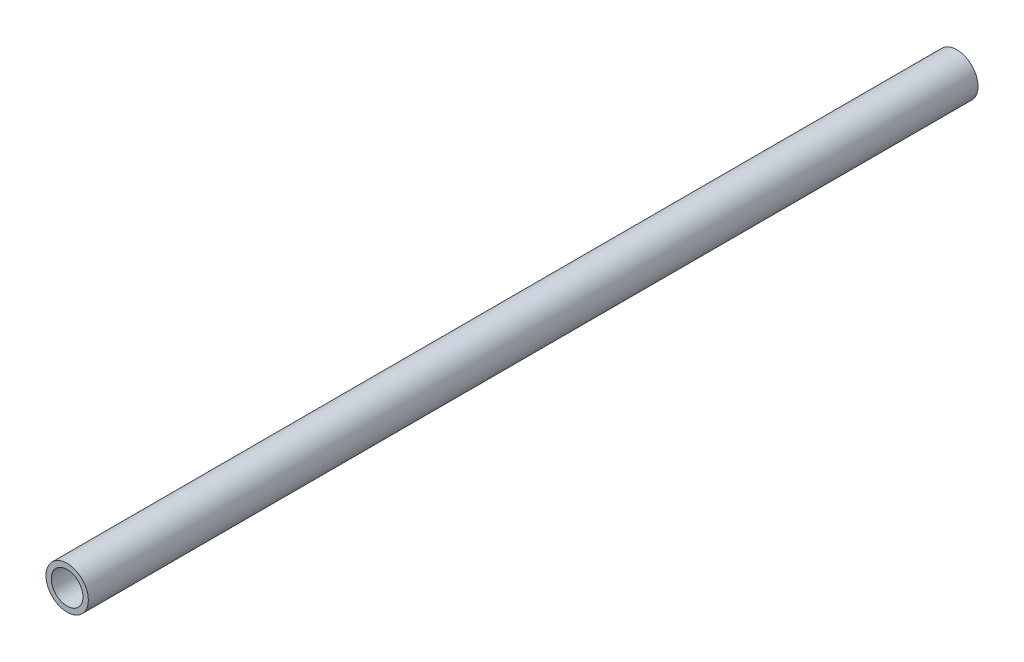
SolidWorks part; units mm, degrees
ref_plane "Front Plane" through (0, 0, 0) normal (0, 0, 1) x (1, 0, 0)
ref_plane "Top Plane" through (0, 0, 0) normal (0, 1, 0) x (1, 0, 0)
ref_plane "Right Plane" through (0, 0, 0) normal (1, 0, 0) x (0, 0, -1)
sketch "Sketch1" plane through (0, 0, 0) normal (0, 0, 1) x (1, 0, 0)
  circle A0 centre (0, 0) radius 9.525
  circle A1 centre (0, 0) radius 12.7
  dimension "D1" = 19.05
  dimension "D2" = 25.4
extrude "Boss-Extrude1" add sketch "Sketch1" along normal blind 533.4
